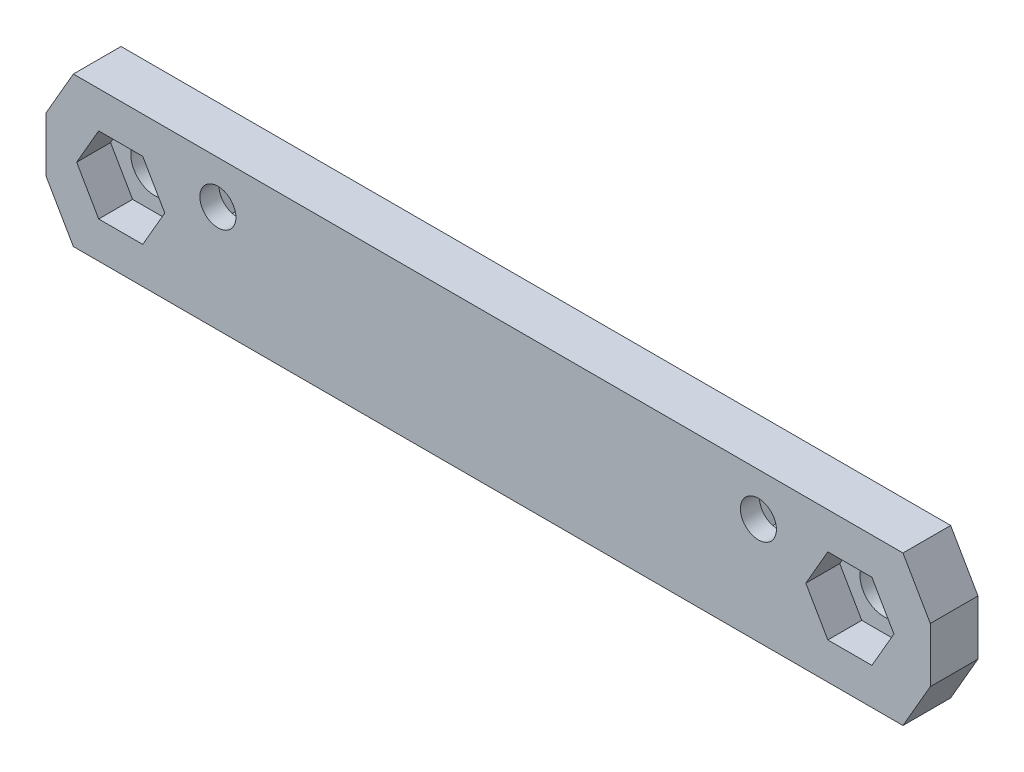
SolidWorks part; units mm, degrees
ref_plane "Front Plane" through (0, 0, 0) normal (0, 0, 1) x (1, 0, 0)
ref_plane "Top Plane" through (0, 0, 0) normal (0, 1, 0) x (1, 0, 0)
ref_plane "Right Plane" through (0, 0, 0) normal (1, 0, 0) x (0, 0, -1)
sketch "Sketch1" plane through (0, 0, 0) normal (0, 0, 1) x (1, 0, 0)
  line L1 (46, -37.5) -> (-46, -37.5)
  line L2 (46, -37.5) -> (46, 37.5)
  line L3 (46, 37.5) -> (-46, 37.5)
  line L4 (-46, -37.5) -> (-46, 37.5)
  line L5 (46, -37.5) -> (-46, 37.5) construction
  line L6 (46, 37.5) -> (-46, -37.5) construction
  point P0 (0, 0)
  dimension "D1" = 92
  dimension "D2" = 75
extrude "Boss-Extrude1" add sketch "Sketch1" along normal blind 4.5
sketch "Sketch2" plane through (0, 0, 4.5) normal (0, 0, 1) x (1, 0, 0)
  line L0 (-34.6699, -1.6) -> (34.1301, -1.6) construction
  line L1 (46, 37.5) -> (-46, 37.5) construction
  dimension "D1" = 39.1
  dimension "D2" = 34.1301
  dimension "D3" = 68.8
hole_wizard "M4 Clearance Hole1" positions "Sketch3" profile "Sketch4" hole size "M4" standard "DIN" end condition through all
sketch "Sketch3" plane through (0, 0, 4.5) normal (0, 0, 1) x (1, 0, 0)
  point P0 (-34.6699, -1.6)
  point P3 (34.1301, -1.6)
sketch "Sketch4" plane through (-34.6699, -1.6, 4.5) normal (1, 0, 0) x (0, -1, 0)
  line L0 (0, 0) -> (0, 4.5)
  line L1 (0, 4.5) -> (2.25, 4.5)
  line L2 (2.25, 4.5) -> (2.25, 0)
  line L5 (2.25, 0) -> (0, 0)
  line L11 (0, -6.35) -> (0, 107.95) construction
  dimension "Thru Hole Dia." = 4.5
  dimension "Thru Hole Depth" = 4.5
sketch "Sketch5" plane through (0, 0, 4.5) normal (0, 0, 1) x (1, 0, 0)
  line L0 (-25.5, 1.4) -> (25.5, 1.4)
  line L2 (-34.6699, -1.6) -> (34.1301, -1.6) construction
  dimension "D1" = 51
  dimension "D2" = 25.5
  dimension "D3" = 3
hole_wizard "M3 Clearance Hole1" positions "Sketch6" profile "Sketch7" hole size "M3" standard "DIN" end condition through all
sketch "Sketch6" plane through (0, 0, 4.5) normal (0, 0, 1) x (1, 0, 0)
  point P0 (-25.5, 1.4)
  point P3 (25.5, 1.4)
sketch "Sketch7" plane through (-25.5, 1.4, 4.5) normal (1, 0, 0) x (0, -1, 0)
  line L0 (0, 0) -> (0, 4.5)
  line L1 (0, 4.5) -> (1.7, 4.5)
  line L2 (1.7, 4.5) -> (1.7, 0)
  line L5 (1.7, 0) -> (0, 0)
  line L11 (0, -6.35) -> (0, 107.95) construction
  dimension "Thru Hole Dia." = 3.4
  dimension "Thru Hole Depth" = 4.5
sketch "Sketch8" plane through (0, 0, 4.5) normal (0, 0, 1) x (1, 0, 0)
  line L1 (-30.513, -1.6) -> (-32.5914, 2)
  line L2 (-32.5914, 2) -> (-36.7483, 2)
  line L3 (-36.7483, 2) -> (-38.8268, -1.6)
  line L4 (-38.8268, -1.6) -> (-36.7483, -5.2)
  line L5 (-36.7483, -5.2) -> (-32.5914, -5.2)
  line L6 (-32.5914, -5.2) -> (-30.513, -1.6)
  line L7 (29.9732, -1.6) -> (32.0517, -5.2)
  line L8 (32.0517, -5.2) -> (36.2086, -5.2)
  line L9 (36.2086, -5.2) -> (38.287, -1.6)
  line L10 (38.287, -1.6) -> (36.2086, 2)
  line L11 (36.2086, 2) -> (32.0517, 2)
  line L12 (32.0517, 2) -> (29.9732, -1.6)
  circle A0 centre (-34.6699, -1.6) radius 3.6 construction
  circle A1 centre (34.1301, -1.6) radius 3.6 construction
  dimension "D1" = 7.2
extrude "Cut-Extrude1" cut sketch "Sketch8" against normal blind 3.2
sketch "Sketch9" plane through (0, 0, 0) normal (0, 0, -1) x (-1, 0, 0)
  line L1 (-22.2091, 1.4) -> (-23.8546, 4.25)
  line L2 (-23.8546, 4.25) -> (-27.1454, 4.25)
  line L3 (-27.1454, 4.25) -> (-28.7909, 1.4)
  line L4 (-28.7909, 1.4) -> (-27.1454, -1.45)
  line L5 (-27.1454, -1.45) -> (-23.8546, -1.45)
  line L6 (-23.8546, -1.45) -> (-22.2091, 1.4)
  line L7 (22.2091, 1.4) -> (23.8546, -1.45)
  line L8 (23.8546, -1.45) -> (27.1454, -1.45)
  line L9 (27.1454, -1.45) -> (28.7909, 1.4)
  line L10 (28.7909, 1.4) -> (27.1454, 4.25)
  line L11 (27.1454, 4.25) -> (23.8546, 4.25)
  line L12 (23.8546, 4.25) -> (22.2091, 1.4)
  circle A0 centre (-25.5, 1.4) radius 2.85 construction
  circle A1 centre (25.5, 1.4) radius 2.85 construction
  dimension "D1" = 5.7
extrude "Cut-Extrude2" cut sketch "Sketch9" against normal blind 2.7
sketch "Sketch10" plane through (0, 0, 0) normal (0, 0, -1) x (-1, 0, 0)
  line L0 (46, 37.5) -> (46, -37.5) construction
  line L1 (-46, 37.5) -> (46, 37.5)
  line L2 (-46, 37.5) -> (-46, 8.25)
  line L3 (-46, 8.25) -> (46, 8.25)
  line L4 (46, 37.5) -> (46, 8.25)
  line L5 (-23.8546, 4.25) -> (-27.1454, 4.25) construction
  line L6 (-46, -37.5) -> (46, -37.5)
  line L7 (-46, -37.5) -> (-46, -9.2)
  line L8 (-46, -9.2) -> (46, -9.2)
  line L9 (46, -37.5) -> (46, -9.2)
  line L10 (-32.0517, -5.2) -> (-36.2086, -5.2) construction
  dimension "D1" = 4
  dimension "D2" = 4
extrude "Cut-Extrude3" cut sketch "Sketch10" against normal through all
sketch "Sketch11" plane through (0, 0, 4.5) normal (0, 0, 1) x (1, 0, 0)
  line L0 (-39.1394, 5.45) -> (-41.7199, 0.9805)
  line L3 (-41.7199, 0.9805) -> (-41.7199, -4.1805)
  line L4 (-41.7199, -4.1805) -> (-39.1394, -8.65)
  line L6 (-39.1394, -8.65) -> (0, -8.65)
  line L7 (0, -8.65) -> (0, -18.65)
  line L8 (0, -18.65) -> (-51, -18.65)
  line L9 (-51, -18.65) -> (-51, 15.45)
  line L10 (-51, 15.45) -> (0, 15.45)
  line L12 (-39.1394, 5.45) -> (0, 5.45)
  line L13 (0, 5.45) -> (0, 15.45)
  line L14 (-36.7483, 2) -> (-38.8268, -1.6) construction
  line L15 (-38.8268, -1.6) -> (-36.7483, -5.2) construction
  line L16 (-27.1454, 4.25) -> (-23.8546, 4.25) construction
  line L18 (-36.7483, -5.2) -> (-32.5914, -5.2) construction
  line L20 (-46, 8.25) -> (-46, -9.2) construction
  point P4 (-36.7529, 5.45)
  point P5 (-37.2887, -8.3388)
  point P9 (-37.2887, 5.45)
  point P10 (-41.7199, -1.6)
  point P21 (-46, -2.9879)
  dimension "D1" = 1.2
  dimension "D2" = 3.45
  dimension "D3" = 7.05
  dimension "D4" = 7.05
  dimension "D5" = 46
  dimension "D6" = 10
  dimension "D7" = 10
  dimension "D8" = 5
extrude "Cut-Extrude4" cut sketch "Sketch11" against normal blind 10
mirror "Mirror1" about plane through (0, 0, 0) normal (1, 0, 0) of "Cut-Extrude4"
